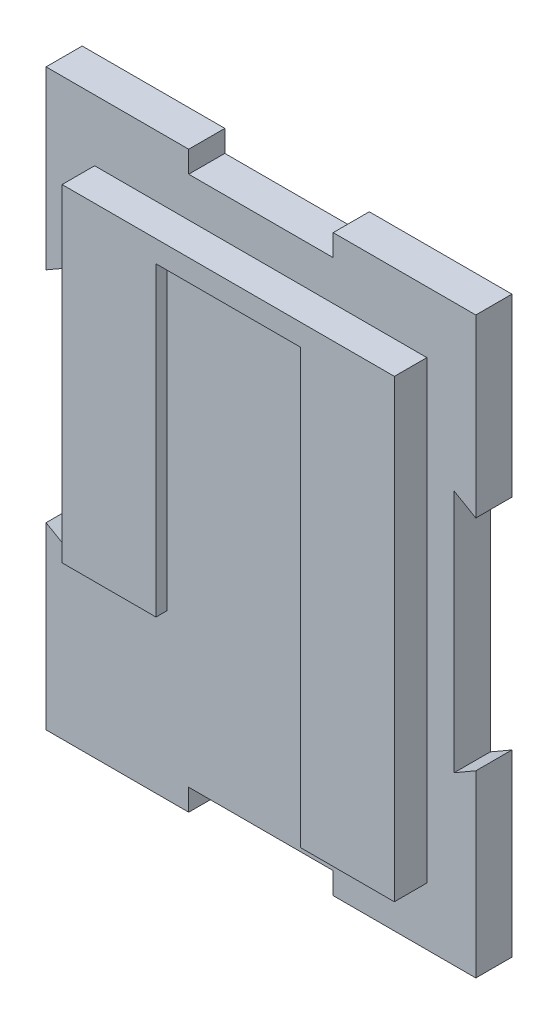
SolidWorks part; units mm, degrees
ref_plane "Front Plane" through (0, 0, 0) normal (1, 0, 0) x (0, 1, 0)
ref_plane "Top Plane" through (0, 0, 0) normal (0, 0, 1) x (0, 1, 0)
ref_plane "Right Plane" through (0, 0, 0) normal (0, 1, 0) x (-1, 0, 0)
sketch "Sketch4" plane through (0, 0, 0) normal (0, 0, 1) x (0, 1, 0)
  line L0 (0.25, -56) -> (-16.6375, -26.75)
  line L1 (-39.75, -29.75) -> (39.75, -29.75)
  line L2 (-39.75, -29.75) -> (-39.75, 29.75)
  line L3 (-39.75, 29.75) -> (39.75, 29.75)
  line L4 (39.75, -29.75) -> (39.75, 29.75)
  line L5 (-39.75, -29.75) -> (39.75, 29.75) construction
  line L6 (-39.75, 29.75) -> (39.75, -29.75) construction
  line L7 (-16.6375, -26.75) -> (17.1375, -26.75)
  line L8 (17.1375, -26.75) -> (0.25, -56)
  line L32 (-55, 0) -> (55, 0) construction
  line L33 (-16.6375, 26.75) -> (17.1375, 26.75)
  line L34 (17.1375, 26.75) -> (0.25, 56)
  line L35 (0.25, 56) -> (-16.6375, 26.75)
  line L36 (0, -55) -> (0, 55) construction
  line L37 (-42.75, -10) -> (-36.75, -10)
  line L38 (-42.75, -10) -> (-42.75, 10)
  line L39 (-42.75, 10) -> (-36.75, 10)
  line L40 (-36.75, -10) -> (-36.75, 10)
  line L41 (-42.75, -10) -> (-36.75, 10) construction
  line L42 (-42.75, 10) -> (-36.75, -10) construction
  line L43 (36.75, -10) -> (36.75, 10)
  line L44 (42.75, 10) -> (36.75, -10) construction
  line L45 (42.75, -10) -> (36.75, 10) construction
  line L46 (42.75, 10) -> (36.75, 10)
  line L47 (42.75, -10) -> (42.75, 10)
  line L48 (42.75, -10) -> (36.75, -10)
  circle A1 centre (0.25, -36.5) radius 9.75
  circle A9 centre (0.25, 36.5) radius 9.75
  point P0 (0, 0)
  point P18 (-39.75, 0)
  dimension "D3" = 20
  dimension "D4" = 19.5
  dimension "D5" = 79.5
  dimension "D1" = 6
  dimension "D2" = 40
  dimension "D6" = 59.5
  dimension "D8" = 3
extrude "Boss-Extrude1" add sketch "Sketch4" along normal blind 5
sketch "Sketch5" plane through (0, 0, 5) normal (0, 0, 1) x (1, 0, 0)
  line L1 (-26, -36) -> (26, -36)
  line L2 (-26, -36) -> (-26, 36)
  line L3 (-26, 36) -> (26, 36)
  line L4 (26, -36) -> (26, 36)
  line L5 (-26, -36) -> (26, 36) construction
  line L6 (-26, 36) -> (26, -36) construction
  point P0 (0, 0)
  dimension "D1" = 72
  dimension "D2" = 52
sketch "Sketch6" plane through (0, -36.75, 0) normal (0, -1, 0) x (1, 0, 0)
  line L0 (-10, 5) -> (-29.75, 5) construction
  line L1 (-20.0286, 5) -> (-23.0286, 5)
  line L2 (-20.0286, 5) -> (-20.0286, 9.5)
  line L3 (-20.0286, 9.5) -> (-23.0286, 9.5)
  line L4 (-23.0286, 5) -> (-23.0286, 9.5)
  line L5 (29.75, 5) -> (10, 5) construction
  line L6 (-23.0286, 9.5) -> (-10.0286, 9.5)
  line L7 (-23.0286, 9.5) -> (-23.0286, 8)
  line L8 (-23.0286, 8) -> (-10.0286, 8)
  line L9 (-10.0286, 9.5) -> (-10.0286, 8)
  line L10 (22.9714, 5) -> (19.9714, 5)
  line L11 (22.9714, 5) -> (22.9714, 9.5)
  line L12 (22.9714, 9.5) -> (19.9714, 9.5)
  line L13 (19.9714, 5) -> (19.9714, 9.5)
  line L15 (22.9714, 9.5) -> (9.9714, 9.5)
  line L16 (22.9714, 9.5) -> (22.9714, 8)
  line L17 (22.9714, 8) -> (9.9714, 8)
  line L18 (9.9714, 9.5) -> (9.9714, 8)
  dimension "D1" = 3
  dimension "D2" = 1.5
  dimension "D3" = 3
  dimension "D4" = 1.5
  dimension "D5" = 40
  dimension "D6" = 10
  dimension "D7" = 10
  dimension "D8" = 3
  dimension "D9" = 3
extrude "Boss-Extrude2" add sketch "Sketch6" against normal blind 60 from offset 5 contours L7 L8 L9 L6 | L3 L2 L1 L4 | L11 L10 L13 L12 | L16 L17 L18 L15 offset against normal yes
sketch "Sketch7" plane through (0, 28.25, 0) normal (0, 1, 0) x (-1, 0, 0)
  line L1 (-22.9714, 5) -> (23.0286, 5)
  line L2 (-22.9714, 5) -> (-22.9714, 9.5)
  line L3 (-22.9714, 9.5) -> (23.0286, 9.5)
  line L4 (23.0286, 5) -> (23.0286, 9.5)
extrude "Boss-Extrude3" add sketch "Sketch7" along normal blind 3
sketch "Sketch8" plane through (0, 0, 0) normal (0, 0, -1) x (1, 0, 0)
  line L1 (-25, -35) -> (25, -35)
  line L2 (-25, -35) -> (-25, 35)
  line L3 (-25, 35) -> (25, 35)
  line L4 (25, -35) -> (25, 35)
  line L5 (-25, -35) -> (25, 35) construction
  line L6 (-25, 35) -> (25, -35) construction
  point P0 (0, 0)
  dimension "D1" = 50
  dimension "D2" = 70
extrude "Cut-Extrude2" cut sketch "Sketch8" against normal blind 1 contours L1 L4 L3 L2
sketch "Sketch9" plane through (0, 0, 1) normal (0, 0, -1) x (1, 0, 0)
  line L0 (-19.9096, -6.3828) -> (19.7925, -6.3828) construction
  line L1 (0, -2.75) -> (0, 2.75) construction
  circle A0 centre (-12.7865, -17.0786) radius 1
  circle A1 centre (-6.4634, -17.0786) radius 1
  circle A2 centre (0, -17.0786) radius 1
  circle A3 centre (0, -14.1256) radius 1
  circle A4 centre (2.9401, -14.1256) radius 1
  circle A5 centre (2.9401, -11.3466) radius 1
  circle A6 centre (6.561, -11.3466) radius 1
  circle A7 centre (12.3436, -11.3466) radius 1
  circle A8 centre (12.3436, -14.1256) radius 1
  circle A9 centre (12.3436, -17.0786) radius 1
  circle A10 centre (15.4241, -11.3466) radius 1
  text T0 "TAP" font "Segoe UI" height in points 48
  dimension "D1" = 2
  dimension "D2" = 2
  dimension "D3" = 2
  dimension "D4" = 2
  dimension "D5" = 2
  dimension "D6" = 2
  dimension "D7" = 2
  dimension "D8" = 2
  dimension "D9" = 2
  dimension "D10" = 2
  dimension "D11" = 2
extrude "Boss-Extrude4" add sketch "Sketch9" along normal blind 1
sketch "Sketch10" plane through (0, 0, 9.5) normal (0, 0, 1) x (1, 0, 0)
  line L1 (-23.0286, -31.75) -> (-10.0219, -31.75)
  line L2 (-23.0286, -31.75) -> (-23.0286, -14.1108)
  line L3 (-23.0286, -14.1108) -> (-10.0219, -14.1108)
  line L4 (-10.0219, -31.75) -> (-10.0219, -14.1108)
extrude "Cut-Extrude3" cut sketch "Sketch10" against normal up to surface (4.5 mm away) up to face at (0, 0.1, 5)
